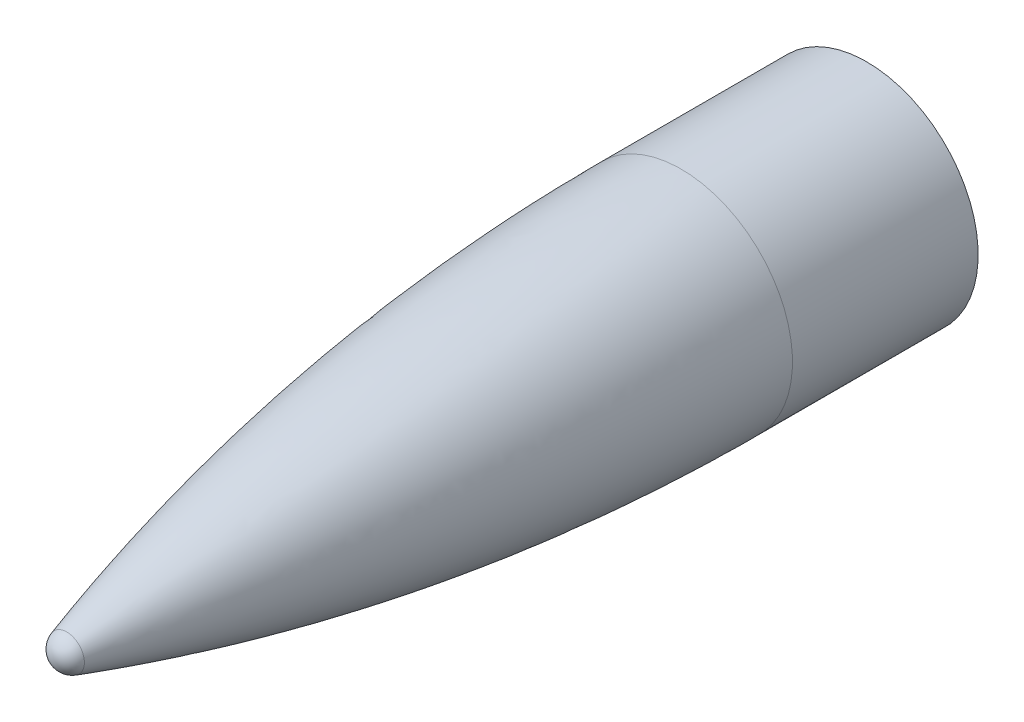
SolidWorks part; units mm, degrees
ref_plane "Front Plane" through (0, 0, 0) normal (0, 0, 1) x (1, 0, 0)
ref_plane "Top Plane" through (0, 0, 0) normal (0, 1, 0) x (1, 0, 0)
ref_plane "Right Plane" through (0, 0, 0) normal (1, 0, 0) x (0, 0, -1)
sketch "Sketch1" plane through (0, 0, 0) normal (1, 0, 0) x (0, 0, -1)
  line L0 (457.2, 76.2) -> (457.2, 0)
  line L3 (28.1027, 0) -> (457.2, 0)
  arc A0 (37.0172, 12.1227) -> (28.1027, 0) centre (40.8027, 0) ccw
  spline S0 degree 4 poles (-3.3203, -1.143) (-2.6894, -0.925) (-1.4274, -0.4896) (1.0985, 0.378) (4.8888, 1.6695) (9.3184, 3.163) (14.3673, 4.8442) (18.7876, 6.2974) (22.5589, 7.5244) (25.7093, 8.5405) (28.1891, 9.3355) (30.795, 10.1647) (33.0499, 10.8791) (36.2132, 11.872) (37.7495, 12.3518) (40.8168, 13.3048) (42.752, 13.9007) (44.596, 14.4663) (47.0311, 15.2099) (50.0648, 16.1302) (54.0196, 17.3184) (58.8883, 18.762) (64.9826, 20.5452) (72.305, 22.6495) (80.8629, 25.0535) (90.6626, 27.7301) (99.2543, 30.0104) (106.63, 31.9206) (114.0148, 33.7954) (121.4085, 35.6347) (134.9838, 38.9253) (154.7863, 43.4742) (194.5403, 51.9052) (254.6036, 62.3984) (312.6193, 69.5415) (364.554, 73.4158) (394.9972, 74.8428) (403.8792, 75.195) (408.9553, 75.378) (414.032, 75.5427) (419.1093, 75.6891) (424.187, 75.8172) (428.6305, 75.9133) (432.4393, 75.9842) (435.6136, 76.0357) (438.1527, 76.0723) (440.693, 76.1043) (443.2303, 76.1318) (445.7763, 76.1546) (448.2963, 76.1729) (450.9016, 76.1867) (453.222, 76.1958) (456.4253, 76.2004) (458.0286, 76.2004) (461.3091, 76.1956) (463.6594, 76.1859) (466.3598, 76.1714) (468.9388, 76.1521) (471.5608, 76.1279) (474.1668, 76.0989) (477.4474, 76.0564) (481.3938, 75.9954) (486.0101, 75.9097) (490.633, 75.8065) (494.5958, 75.7057) (497.2372, 75.6319) (498.5579, 75.5933) (499.2183, 75.5737) knots 0 0 0 0 0 0.005224 0.010448 0.020895 0.031343 0.041791 0.052112 0.057273 0.062433 0.067594 0.072754 0.077915 0.083075 0.088044 0.093012 0.097981 0.100465 0.102949 0.112886 0.122824 0.132761 0.142698 0.162572 0.182446 0.20232 0.222194 0.232131 0.242068 0.261942 0.281816 0.341438 0.40106 0.579927 0.758793 0.798541 0.808478 0.818415 0.828352 0.838289 0.848226 0.858163 0.8681 0.873069 0.878037 0.883006 0.887974 0.892943 0.897911 0.90288 0.907848 0.912817 0.917785 0.922892 0.928 0.933107 0.938214 0.943321 0.948428 0.953535 0.958642 0.968982 0.979321 0.989661 0.99483 1 1 1 1 1 construction
  spline S1 degree 4 poles (37.0172, 12.1227) (37.5231, 12.2807) (38.5383, 12.5969) (40.8168, 13.3048) (42.752, 13.9007) (44.596, 14.4663) (47.0311, 15.2099) (50.0648, 16.1302) (54.0196, 17.3184) (58.8883, 18.762) (64.9826, 20.5452) (72.305, 22.6495) (80.8629, 25.0535) (90.6626, 27.7301) (99.2543, 30.0104) (106.63, 31.9206) (114.0148, 33.7954) (121.4085, 35.6347) (134.9838, 38.9253) (154.7863, 43.4742) (194.5403, 51.9052) (254.6036, 62.3984) (312.6193, 69.5415) (364.554, 73.4158) (394.9972, 74.8428) (403.8792, 75.195) (408.9553, 75.378) (414.032, 75.5427) (419.1093, 75.6891) (424.187, 75.8172) (428.6305, 75.9133) (432.4393, 75.9842) (435.6136, 76.0357) (438.1527, 76.0723) (440.693, 76.1043) (443.2303, 76.1318) (445.7763, 76.1546) (448.2963, 76.1729) (450.9016, 76.1867) (453.222, 76.1958) (455.6079, 76.1992) (456.67, 76.2) (457.2, 76.2) knots 0.083075 0.083075 0.083075 0.083075 0.083075 0.088044 0.093012 0.097981 0.100465 0.102949 0.112886 0.122824 0.132761 0.142698 0.162572 0.182446 0.20232 0.222194 0.232131 0.242068 0.261942 0.281816 0.341438 0.40106 0.579927 0.758793 0.798541 0.808478 0.818415 0.828352 0.838289 0.848226 0.858163 0.8681 0.873069 0.878037 0.883006 0.887974 0.892943 0.897911 0.90288 0.907848 0.912817 0.917785 0.917785 0.917785 0.917785 0.917785
  point P10 (28.1158, -0.5773)
  point P11 (29.0506, 0)
  point P13 (0, 0)
  point P14 (0, 0)
  dimension "D1" = 12.7
ref_axis "Axis1" through (0, 0, -480.06) along (0, 0, 1)
revolve "Revolve1" add sketch "Sketch1" angle 360 about axis through (0, 0, -480.06) along (0, 0, 1)
sketch "Sketch4" plane through (0, 0, -457.2) normal (0, 0, -1) x (-1, 0, 0)
  circle A0 centre (0, 0) radius 76.2
  dimension "D1" = 152.4
extrude "Boss-Extrude1" add sketch "Sketch4" along normal blind 127
equation "\"BodyTubeRadius\"= 3in"
equation "\"OgiveRatio\"= 3"
equation "\"OgiveRadius\"= ( \"BodyTubeRadius\" ^ 2 + ( \"OgiveLength\" ) ^ 2 ) / ( 2 * \"BodyTubeRadius\" )"
equation "\"OgiveLength\"= 2 * \"BodyTubeRadius\" * \"OgiveRatio\""
equation "\"noseRadius\"= .5in"
equation "\"noseCapCenter\"= \"OgiveLength\" - sqr ( ( \"OgiveRadius\" - \"noseRadius\" ) ^ 2 - ( \"OgiveRadius\" - \"BodyTubeRadius\" ) ^ 2 )'center of the sphere that forms that cap"
equation "\"yTangent\"= ( \"noseRadius\" * ( \"OgiveRadius\" - \"BodyTubeRadius\" ) ) / ( \"OgiveRadius\" - \"noseRadius\" )'y location of tangency"
equation "\"xTangent\"= \"noseCapCenter\" - sqr ( \"noseRadius\" ^ 2 - \"yTangent\" ^ 2 )'x location of tangency"
equation "\"D1@Sketch4\"=\"BodyTubeRadius\"*2"
equation "\"BodyTubeLength\"= 5in"
